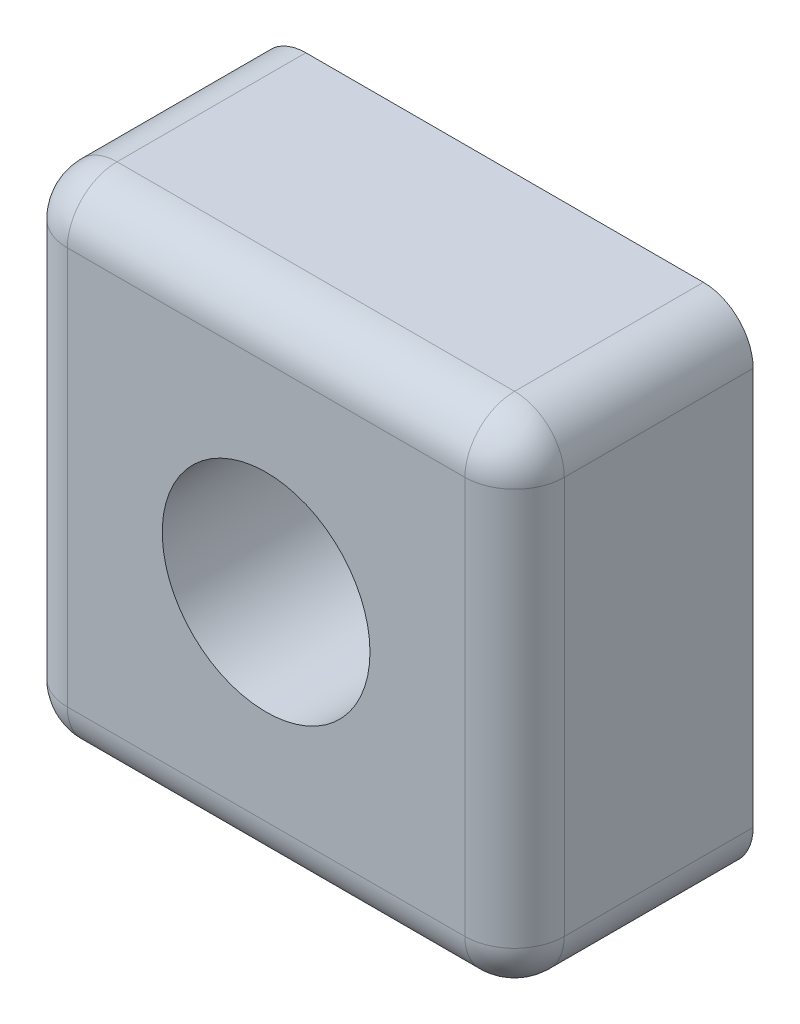
SolidWorks part; units mm, degrees
ref_plane "前视基准面" through (0, 0, 0) normal (0, 0, 1) x (1, 0, 0)
ref_plane "上视基准面" through (0, 0, 0) normal (0, 1, 0) x (1, 0, 0)
ref_plane "右视基准面" through (0, 0, 0) normal (1, 0, 0) x (0, 0, -1)
sketch "草图1" plane through (0, 0, 0) normal (0, 0, 1) x (1, 0, 0)
  line L0 (0, 0) -> (0, 48.2102) construction
  line L1 (50, -50) -> (50, 50)
  line L2 (50, 0) -> (-50, 0)
  line L3 (0, 0) -> (0, 50)
  line L4 (50, 50) -> (-50, 50)
  line L5 (-50, -50) -> (-50, 50)
  line L6 (50, -50) -> (-50, -50)
  line L7 (0, -25) -> (150, -25)
  line L8 (0, 0) -> (150, 0)
  line L9 (0, -25) -> (0, 25)
  line L10 (0, 25) -> (150, 25)
  line L11 (150, -25) -> (150, 25)
  circle A0 centre (0, 0) radius 20.9
  dimension "D1" = 41.8
  dimension "D2" = 50
  dimension "D3" = 50
  dimension "D4" = 25
  dimension "D5" = 150
extrude "凸台-拉伸1" add sketch "草图1" along normal blind 48 contours A0 L9 L3 L4 L5 L2 | L6 L0 L9 A0 L2 L5 | L0 L6 L1 L7 | A0 L9 L7 L1 L2 | A0 L2 L1 L10 L9 | L3 L10 L1 L4
fillet "圆角1" radius 10 4 edges at (50, 50, 24) (50, -50, 24) (-50, -50, 24) (-50, 50, 24)
fillet "圆角3" radius 10 8 edges at (50, 0, 48) (47.0711, -47.0711, 48) (0, -50, 48) (-47.0711, -47.0711, 48) (-50, 0, 48) (-47.0711, 47.0711, 48) (0, 50, 48) (47.0711, 47.0711, 48)
